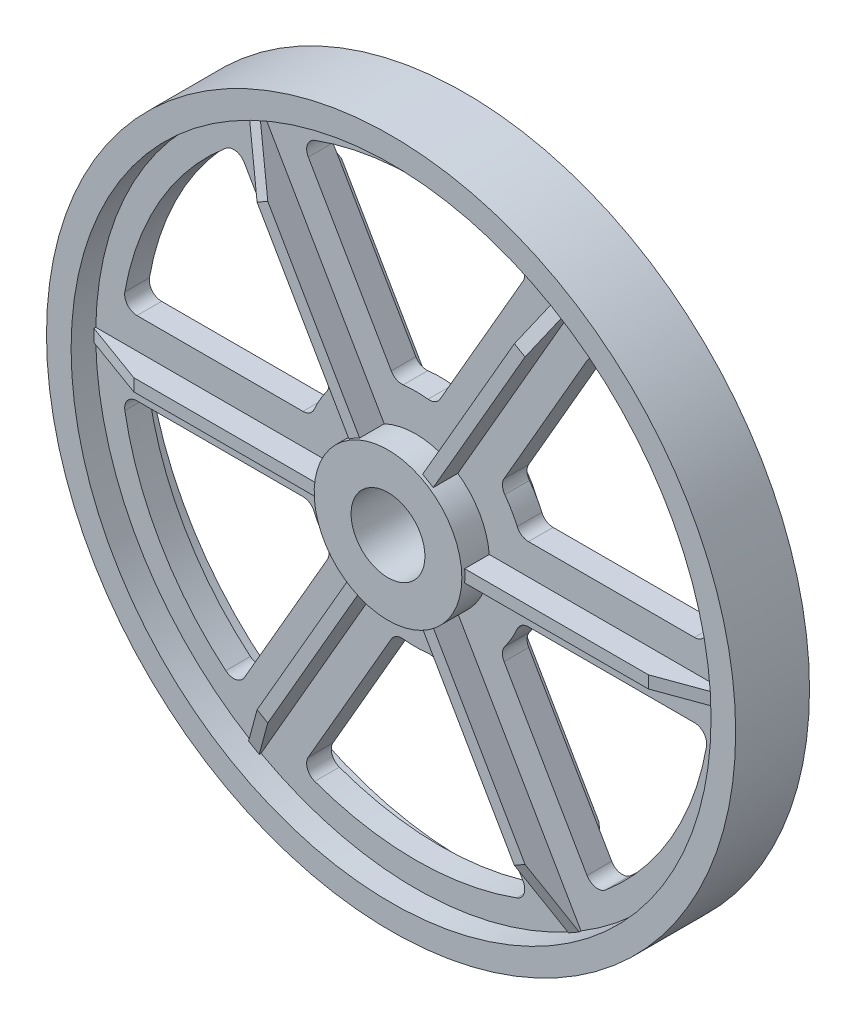
SolidWorks part; units mm, degrees
extrude "CenterHub" add sketch "Sketch1" along normal mid plane 41.275
sketch "Sketch1" plane through (0, 0, 0) normal (0, 0, 1) x (1, 0, 0)
  circle A0 centre (0, 0) radius 38.1
  dimension "D1" = 76.2
revolve "Rim and Web" add sketch "Sketch2" angle 360 about L0
sketch "Sketch2" plane through (0, 0, 0) normal (1, 0, 0) x (0, 0, -1)
  line L0 (0, 0) -> (51.266, 0) construction
  line L1 (-6.35, 0) -> (6.35, 0)
  line L2 (-6.35, 0) -> (-6.35, 165.1)
  line L3 (-6.35, 165.1) -> (-19.05, 165.1)
  line L4 (6.35, 165.1) -> (6.35, 0)
  line L5 (-19.05, 177.8) -> (19.05, 177.8)
  line L6 (-19.05, 177.8) -> (-19.05, 165.1)
  line L7 (19.05, 165.1) -> (6.35, 165.1)
  line L8 (19.05, 165.1) -> (19.05, 177.8)
  line L9 (0, 0) -> (0, 95.9354) construction
  dimension "D1" = 355.6
  dimension "D2" = 12.7
  dimension "D3" = 38.1
  dimension "D4" = 12.7
material "Gray Cast Iron"
ref_plane "Plane1" through (0, 0, 0) normal (0, 0, 1) x (1, 0, 0)
ref_plane "Plane2" through (0, 0, 0) normal (0, 1, 0) x (1, 0, 0)
ref_plane "Plane3" through (0, 0, 0) normal (1, 0, 0) x (0, 0, -1)
other "Configuration Table"
sketch "Sketch3" plane through (0, 0, 0) normal (0, 1, 0) x (1, 0, 0)
  line L0 (0, 0) -> (193.8767, 0) construction
  line L1 (0, -19.05) -> (132.747, -19.05)
  line L2 (132.747, -19.05) -> (167.64, -6.35)
  line L3 (165.1, -6.35) -> (-165.1, -6.35) construction
  line L4 (167.64, -6.35) -> (167.64, 6.35)
  line L5 (132.747, 19.05) -> (167.64, 6.35)
  line L6 (0, 19.05) -> (132.747, 19.05)
  line L7 (0, -19.05) -> (0, 19.05)
  line L8 (165.1, -19.05) -> (-165.1, -19.05) construction
  line L9 (165.1, -19.05) -> (165.1, -6.35) construction
  point P10 (167.64, 0)
  dimension "D1" = 20
  dimension "D2" = 2.54
extrude "Rib" add sketch "Sketch3" along normal mid plane 6.35
sketch "Sketch4" plane through (0, 0, 0) normal (0, 0, 1) x (1, 0, 0)
  line L0 (0, 0) -> (202.3803, 0) construction
  line L1 (0, 0) -> (96.4485, -167.0538) construction
  line L2 (92.1001, -121.4221) -> (43.4386, -37.1378)
  line L3 (151.2047, -19.05) -> (53.8815, -19.05)
  circle A1 centre (0, 0) radius 57.15
  arc A3 (43.4386, -37.1378) -> (53.8815, -19.05) centre (0, 0) ccw
  circle A4 centre (0, 0) radius 152.4
  arc A5 (92.1001, -121.4221) -> (151.2047, -19.05) centre (0, 0) ccw
  dimension "D1" = 19.05
  dimension "D2" = 19.05
  dimension "D5" = 60
  dimension "D3" = 19.05
  dimension "D4" = 12.7
extrude "Lightening hole" cut sketch "Sketch4" against normal through all and the other way through all
fillet "Fillet1" radius 6.35 4 edges at (151.2047, -19.05, 0) (92.1001, -121.4221, 0) (43.4386, -37.1378, 0) (53.8815, -19.05, 0)
pattern_circular "CirPattern1" count 6 every 60 about axis through (0, 0, 0) along (0, 0, 1) of "Lightening hole", "Fillet1", "Rib"
sketch "Sketch5" plane through (0, 0, 0) normal (0, 0, 1) x (1, 0, 0)
  circle A0 centre (0, 0) radius 19.05
  dimension "D1" = 38.1
extrude "Thru hole" cut sketch "Sketch5" against normal through all and the other way through all
equation "\"D2@CirPattern1\" = 360 / \"D1@CirPattern1\""
equation "\"D5@Sketch4\" = \"D2@CirPattern1\""
